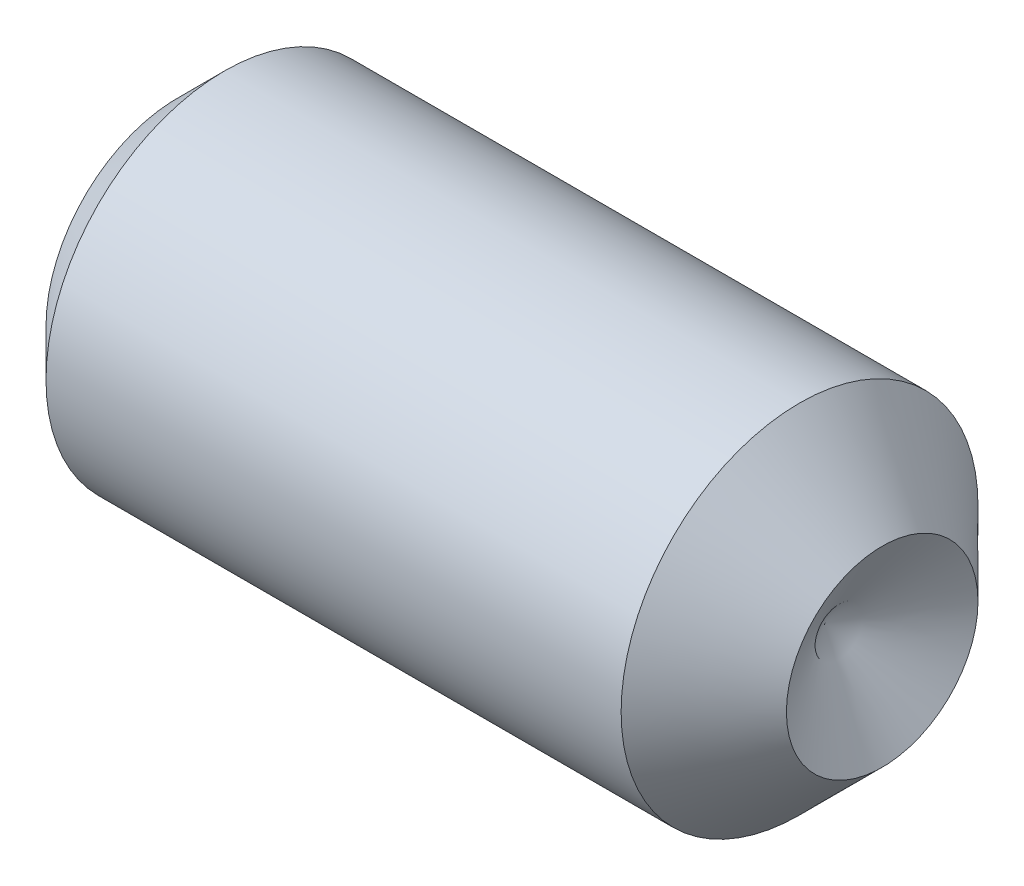
SolidWorks part; units mm, degrees
ref_plane "Plane1" through (0, 0, 0) normal (0, 0, 1) x (1, 0, 0)
ref_plane "Plane2" through (0, 0, 0) normal (0, 1, 0) x (1, 0, 0)
ref_plane "Plane3" through (0, 0, 0) normal (1, 0, 0) x (0, 0, -1)
sketch "BodySke" plane through (0, 0, 0) normal (0, 0, 1) x (1, 0, 0)
  line L0 (0, 0) -> (0, 1.7831)
  line L1 (0, 1.7831) -> (0.6299, 2.413)
  line L2 (0.6299, 2.413) -> (8.4074, 2.413)
  line L3 (8.4074, 2.413) -> (9.525, 1.2954)
  line L4 (8.7466, 0) -> (0, 0)
  line L5 (-12.7, 0) -> (88.9, 0) construction
  line L6 (8.7466, 0) -> (9.525, 1.2954)
  line L7 (9.525, 1.2954) -> (9.525, 10.8204) construction
  line L8 (0, -1.7831) -> (0.6299, -2.413) construction
  line L9 (8.7466, 0) -> (9.525, -1.2954) construction
  line L10 (8.4074, -2.413) -> (9.525, -1.2954) construction
  line L11 (1.0592, 15.875) -> (1.0592, -3.175) construction
  dimension "Length" = 9.525
  dimension "Diameter" = 4.826
  dimension "Drive_ch_ang" = 45
  dimension "Minor_dia" = 3.5662
  dimension "Cup_nose_ang" = 45
  dimension "Cup_ang" = 118
  dimension "Cup_dia" = 2.5908
  dimension "Advance" = 1.0592
revolve "BaseBody" add sketch "BodySke" angle 360 about L5
cosmetic thread "ThreadCosmetic" [suppressed] parameters "Thread_minor"=3.5662
sketch "Sketch2" plane through (0, 0, 0) normal (-1, 0, 0) x (0, 0, 1)
  line L0 (0.687, 1.19) -> (-0.687, 1.19)
  line L1 (-0.687, 1.19) -> (-1.3741, 0)
  line L2 (0.687, 1.19) -> (1.3741, 0)
  line L3 (0.687, -1.19) -> (1.3741, 0)
  line L4 (0.687, -1.19) -> (-0.687, -1.19)
  line L5 (-0.687, -1.19) -> (-1.3741, 0)
  dimension "Hex_size" = 2.38
  dimension "D2" = 1.19
  dimension "D3" = 1.19
extrude "Hex" cut sketch "Sketch2" against normal blind 2.54
sketch "Sketch4" plane through (0, 4.7709, -0.5249) normal (-1, 0, 0) x (0, 0, 1)
  line L0 (0.5249, -4.7709) -> (1.9854, -4.7709)
  line L1 (0.5249, -4.7709) -> (6.6732, -1.2211) construction
  line L2 (0.5249, -4.7709) -> (1.2551, -3.506)
  line L3 (1.7258, -4.4441) -> (1.9182, -4.333)
  line L4 (1.4083, -3.8942) -> (1.6007, -3.7831)
  arc A0 (1.7258, -4.4441) -> (1.4083, -3.8942) centre (0.5249, -4.7709) ccw
  arc A1 (1.9854, -4.7709) -> (1.9182, -4.333) centre (0.5249, -4.7709) ccw
  arc A2 (1.2551, -3.506) -> (1.6007, -3.7831) centre (0.5249, -4.7709) cw
  circle A3 centre (0.5249, -4.7709) radius 1.2446 construction
  circle A4 centre (0.5249, -4.7709) radius 1.4605 construction
  dimension "D1" = 30
  dimension "Spline_n_dim" = 2.4892
  dimension "Spline_m_dim" = 2.921
  dimension "Spline_a_dim" = 60
  dimension "D3" = 0.3175
  dimension "Spline_p_dim" = 0.635
extrude "Spline" [suppressed] cut sketch "Sketch4" against normal blind 2.032
pattern_circular "CirPattern1" [suppressed] count 6 every 60 about axis through (-12.7, 0, 0) along (1, 0, 0)
sketch "ThdSchSke" plane through (0, 0, 0) normal (0, 0, 1) x (1, 0, 0)
  line L0 (0.6299, -1.7831) -> (0.1888, -2.413)
  line L1 (0.6299, -1.7831) -> (1.071, -2.413)
  line L2 (1.071, -2.413) -> (1.071, -3.0162)
  line L3 (-3.175, 0) -> (5.1513, 0) construction
  line L4 (0.6299, 2.413) -> (0.6299, -2.413) construction
  line L5 (1.071, -3.0162) -> (0.1888, -3.0162)
  line L6 (0.1888, -3.0162) -> (0.1888, -2.413)
  dimension "Thread_minor" = 3.5662
  dimension "Diameter" = 4.826
  dimension "SideAngle" = 55
  dimension "VeeAngle" = 70
  dimension "Overcut" = 6.0325
revolve "ThreadSchematic" [suppressed] cut sketch "ThdSchSke" angle 360 about L3
pattern_linear "ThdSchPat" [suppressed]
equation "\"D2@Sketch2\" = \"Hex_size@Sketch2\" / 2"
equation "\"D3@Sketch2\" = \"Hex_size@Sketch2\" / 2"
equation "\"Thread_minor@ThreadCosmetic\" = \"Minor_dia@BodySke\""
equation "\"D1@Sketch4\" = \"Spline_a_dim@Sketch4\" / 2"
equation "\"D3@Sketch4\" = \"Spline_p_dim@Sketch4\" / 2"
equation "\"D2@CirPattern1\" = \"Spline_a_dim@Sketch4\""
equation "\"Num_teeth@CirPattern1\" = 360 / \"D2@CirPattern1\""
equation "\"Thread_minor@ThdSchSke\" = \"Thread_minor@ThreadCosmetic\""
equation "\"Diameter@ThdSchSke\" = \"Diameter@BodySke\""
equation "\"Overcut@ThdSchSke\" = \"Diameter@BodySke\" * 1.25"
equation "\"Num_threads@ThdSchPat\" = int( (\"Length@BodySke\" - ( ( ( \"Diameter@BodySke\" - \"Minor_dia@BodySke\" ) * 0.5 ) / tan( \"Drive_ch_ang@BodySke\" * 0.017453292 ) ) - ( ( ( \"Diameter@BodySke\" - \"Cup_dia@BodySke\" ) * 0.5 ) * tan( \"Cup_nose_ang@BodySke\" * 0.017453292 ) ) ) / \"Advance@BodySke\" + 0.999 )  + 1"
equation "\"Advance@ThdSchPat\" = (\"Length@BodySke\" - ( ( ( \"Diameter@BodySke\" - \"Minor_dia@BodySke\" ) * 0.5 ) / tan( \"Drive_ch_ang@BodySke\" * 0.017453292 ) ) - ( ( ( \"Diameter@BodySke\" - \"Cup_dia@BodySke\" ) * 0.5 ) * tan( \"Cup_nose_ang@BodySke\" * 0.017453292 ) ) ) /  (\"Num_threads@ThdSchPat\" - 1) 'relax it"
equation "' \"Num_threads@ThdSchPat\" = \"Num_threads@ThdSchPat\" - sgn( \"Num_threads@ThdSchPat\" - 1) '---chamfered tips only---"
